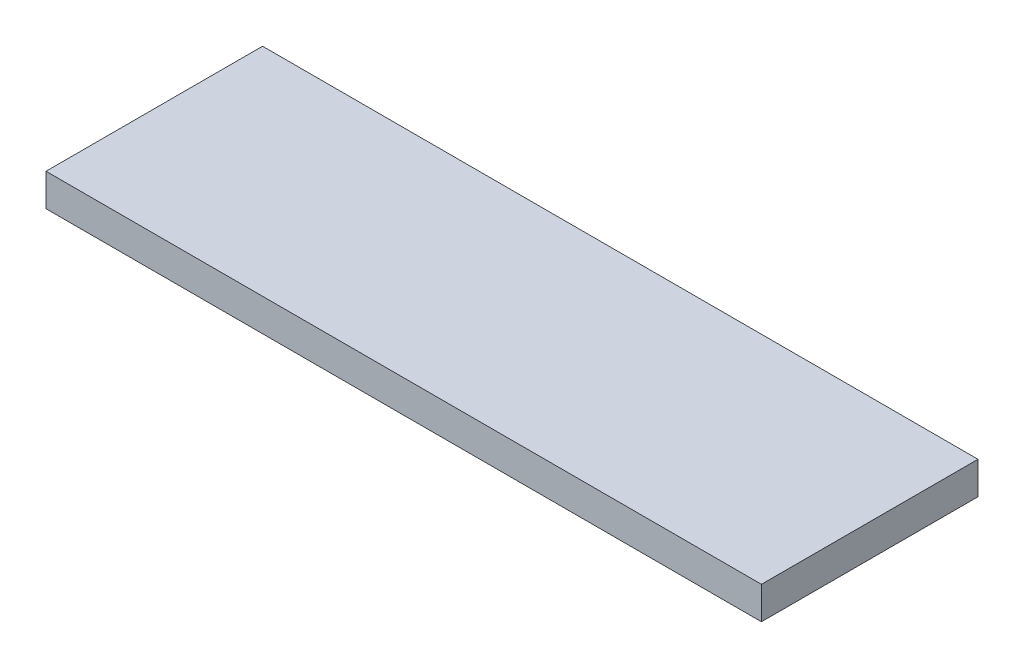
SolidWorks part; units mm, degrees
ref_plane "Front" through (0, 0, 0) normal (0, 0, 1) x (1, 0, 0)
ref_plane "Top" through (0, 0, 0) normal (0, 1, 0) x (1, 0, 0)
ref_plane "Right" through (0, 0, 0) normal (1, 0, 0) x (0, 0, -1)
sketch "Sketch1" plane through (0, 0, 0) normal (0, 1, 0) x (1, 0, 0)
  line L0 (-33.02, 0) -> (33.02, 0) construction
  line L1 (-33.02, 9.9949) -> (33.02, 9.9949)
  line L2 (-33.02, 9.9949) -> (-33.02, -9.9949)
  line L3 (-33.02, -9.9949) -> (33.02, -9.9949)
  line L4 (33.02, 9.9949) -> (33.02, -9.9949)
  line L5 (-33.02, 9.9949) -> (33.02, -9.9949) construction
  line L6 (-33.02, -9.9949) -> (33.02, 9.9949) construction
  line L10 (0, 0) -> (0, 9.9949) construction
  point P0 (0, 0)
  dimension "D1" = 66.04
  dimension "D2" = 19.9898
extrude "Boss-Extrude1" add sketch "Sketch1" along normal blind 2.9972
